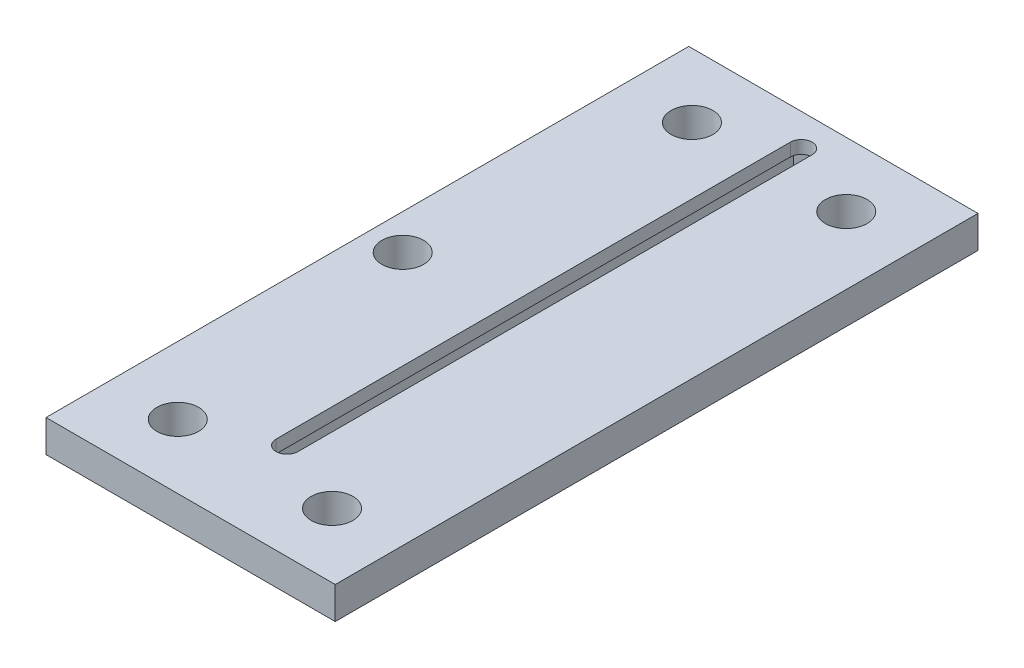
SolidWorks part; units mm, degrees
ref_plane "Front Plane" through (0, 0, 0) normal (0, 0, 1) x (1, 0, 0)
ref_plane "Top Plane" through (0, 0, 0) normal (0, 1, 0) x (1, 0, 0)
ref_plane "Right Plane" through (0, 0, 0) normal (1, 0, 0) x (0, 0, -1)
sketch "Sketch1" plane through (0, 0, 0) normal (0, 1, 0) x (1, 0, 0)
  line L1 (-12, -40) -> (12, -40) construction
  line L2 (-12, -40) -> (-12, 40) construction
  line L3 (-12, 40) -> (12, 40) construction
  line L4 (12, -40) -> (12, 40) construction
  line L5 (-12, -40) -> (12, 40) construction
  line L6 (-12, 40) -> (12, -40) construction
  line L7 (-22.5, -50) -> (22.5, -50)
  line L8 (-22.5, -50) -> (-22.5, 50)
  line L9 (-22.5, 50) -> (22.5, 50)
  line L10 (22.5, -50) -> (22.5, 50)
  line L11 (-22.5, -50) -> (22.5, 50) construction
  line L12 (-22.5, 50) -> (22.5, -50) construction
  circle A0 centre (-12, 40) radius 3.25
  circle A1 centre (12, 40) radius 3.25
  circle A2 centre (12, -40) radius 3.25
  circle A3 centre (-12, -40) radius 3.25
  circle A4 centre (7, 0) radius 3.25 construction
  circle A5 centre (-17, 0) radius 3.25
  point P0 (0, 0)
  point P14 (0, 0)
  dimension "D3" = 6.5
  dimension "D4" = 5
  dimension "D5" = 24
  dimension "D1" = 80
  dimension "D2" = 24
  dimension "D6" = 100
  dimension "D7" = 45
extrude "Boss-Extrude1" add sketch "Sketch1" along normal blind 5
sketch "Sketch2" plane through (0, 5, 0) normal (0, 1, 0) x (1, 0, 0)
  line L0 (-1000, 0) -> (49000, 0) construction
  line L1 (0, 45) -> (0, -35) construction
  line L2 (1.7, 45) -> (1.7, -35)
  line L3 (-1.7, 45) -> (-1.7, -35)
  line L5 (22.5, 50) -> (-22.5, 50) construction
  arc A0 (1.7, 45) -> (-1.7, 45) centre (0, 45) ccw
  arc A1 (-1.7, -35) -> (1.7, -35) centre (0, -35) ccw
  point P5 (0, 5)
  dimension "D3" = 1.7
  dimension "D1" = 80
  dimension "D2" = 5
extrude "Cut-Extrude1" cut sketch "Sketch2" against normal blind 2
sketch "Sketch3" plane through (0, 3, 0) normal (0, 1, 0) x (1, 0, 0)
  line L0 (2.9, 43.3257) -> (2.9, -33.3257)
  line L1 (2.9, 46.6743) -> (0, 48.3486)
  line L2 (0, 48.3486) -> (-2.9, 46.6743)
  line L3 (-2.9, 46.6743) -> (-2.9, 43.3257)
  line L4 (-2.9, 43.3257) -> (0, 41.6514)
  line L5 (0, 41.6514) -> (2.9, 43.3257)
  line L6 (2.9, 43.3257) -> (2.9, 46.6743)
  line L7 (2.9, -33.3257) -> (0, -31.6514)
  line L8 (0, -31.6514) -> (-2.9, -33.3257)
  line L9 (-2.9, -33.3257) -> (-2.9, -36.6743)
  line L10 (-2.9, -36.6743) -> (0, -38.3486)
  line L11 (0, -38.3486) -> (2.9, -36.6743)
  line L12 (2.9, -36.6743) -> (2.9, -33.3257)
  line L13 (-2.9, 43.3257) -> (-2.9, -33.3257)
  circle A0 centre (0, 45) radius 2.9 construction
  circle A1 centre (0, -35) radius 2.9 construction
  arc M3 (1.7, 45) -> (-1.7, 45) centre (0, 45) ccw
  line M4 (-1.7, 45) -> (-1.7, -35)
  arc M5 (-1.7, -35) -> (1.7, -35) centre (0, -35) ccw
  line M6 (1.7, -35) -> (1.7, 45)
  dimension "D1" = 5.8
extrude "Cut-Extrude2" cut sketch "Sketch3" against normal up to next contours L4 L5 M6 M3 M4 | L8 L7 L5 L4 M6 M4 | L7 L8 M4 M5 M6 | L4 L13 L8 M4 | L7 L0 L5 M6 | L5 L6 L1 L2 L3 L4 M4 M3 M6 | L11 L12 L7 L8 L9 L10 M6 M5 M4
mirror "Mirror1" [suppressed] about plane through (0, 0, 0) normal (0, 0, 1)
